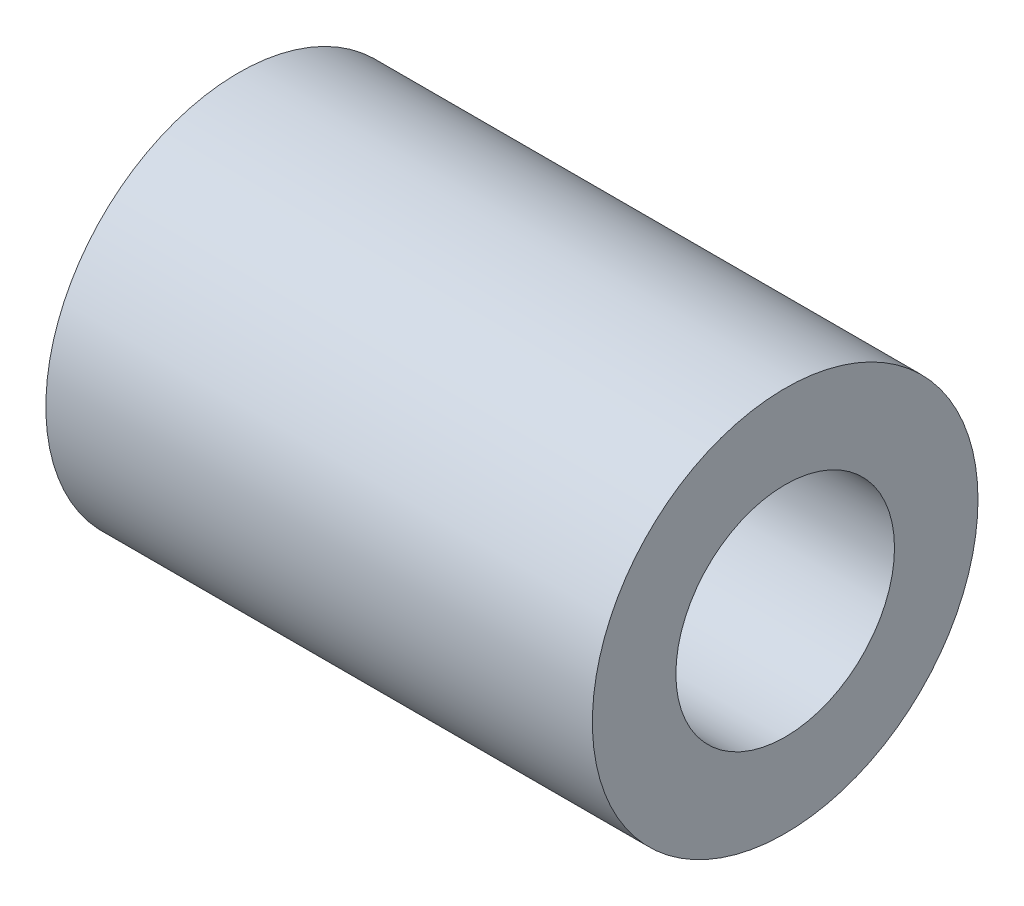
SolidWorks part; units mm, degrees
ref_plane "Front Plane" through (0, 0, 0) normal (0, 0, 1) x (1, 0, 0)
ref_plane "Top Plane" through (0, 0, 0) normal (0, 1, 0) x (1, 0, 0)
ref_plane "Right Plane" through (0, 0, 0) normal (1, 0, 0) x (0, 0, -1)
sketch "Sketch1" plane through (0, 0, 0) normal (1, 0, 0) x (0, 0, -1)
  circle A0 centre (0, 0) radius 1.8
  circle A1 centre (0, 0) radius 3.175
  dimension "D1" = 3.6
  dimension "D2" = 6.35
extrude "Boss-Extrude1" add sketch "Sketch1" along normal blind 9
